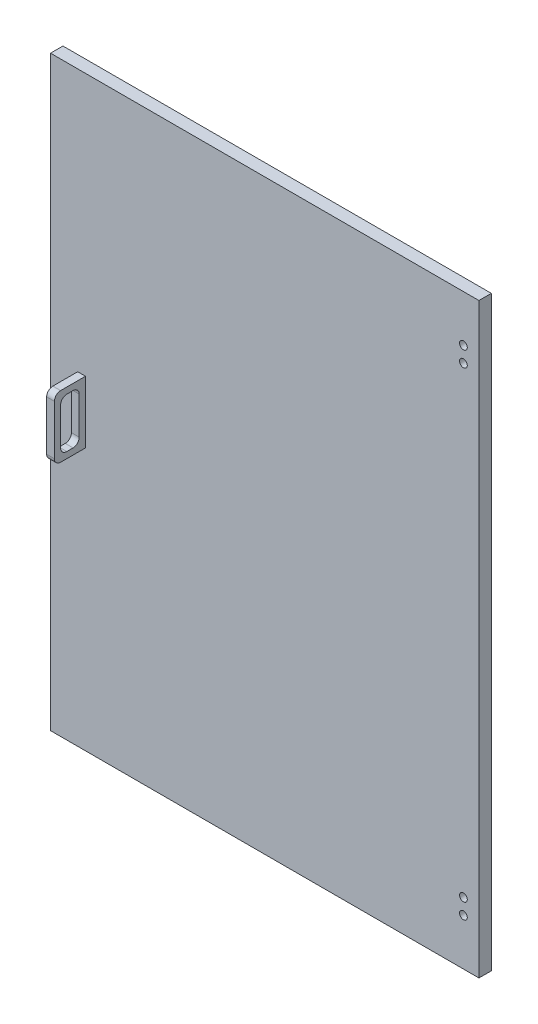
SolidWorks part; units mm, degrees
material "PVC 0.007 Plasticized"
ref_plane "Front Plane" through (0, 0, 0) normal (0, 0, 1) x (1, 0, 0)
ref_plane "Top Plane" through (0, 0, 0) normal (0, 1, 0) x (1, 0, 0)
ref_plane "Right Plane" through (0, 0, 0) normal (1, 0, 0) x (0, 0, -1)
sketch "Sketch1" plane through (0, 0, 0) normal (0, 0, 1) x (1, 0, 0)
  line L0 (-87.63, 120.015) -> (87.63, 120.015)
  line L7 (-87.63, 120.015) -> (-87.63, -120.015)
  line L8 (-87.63, -120.015) -> (87.63, -120.015)
  line L9 (87.63, 120.015) -> (87.63, -120.015)
  point P0 (0, 0)
  dimension "D1" = 240.03
  dimension "D2" = 175.26
  dimension "D3" = 87.63
  dimension "D4" = 120.015
extrude "Boss-Extrude1" add sketch "Sketch1" against normal blind 5.08
sketch "Sketch2" plane through (0, 0, 0) normal (0, 0, 1) x (1, 0, 0)
  line L0 (87.63, -120.015) -> (87.63, 120.015) construction
  line L1 (87.63, 120.015) -> (-87.63, 120.015) construction
  line L2 (2.794, 0) -> (-2.794, 0) construction
  circle A0 centre (81.28, 100.965) radius 1.5875
  circle A1 centre (81.28, 94.615) radius 1.5875
  circle A2 centre (81.28, -94.615) radius 1.5875
  circle A3 centre (81.28, -100.965) radius 1.5875
  point P10 (81.28, -94.615)
  dimension "D1" = 3.175
  dimension "D2" = 3.175
  dimension "D3" = 6.35
  dimension "D4" = 19.05
  dimension "D5" = 6.35
extrude "Cut-Extrude1" cut sketch "Sketch2" against normal through all
sketch "Sketch3" plane through (0, 0, 0) normal (0, 0, 1) x (1, 0, 0)
  line L0 (2.794, 0) -> (-2.794, 0) construction
  line L1 (-76.5175, -12.7) -> (-73.3425, -12.7)
  line L2 (-76.5175, -12.7) -> (-76.5175, 12.7)
  line L3 (-76.5175, 12.7) -> (-73.3425, 12.7)
  line L4 (-73.3425, -12.7) -> (-73.3425, 12.7)
  line L5 (-76.5175, -12.7) -> (-73.3425, 12.7) construction
  line L6 (-76.5175, 12.7) -> (-73.3425, -12.7) construction
  line L7 (-87.63, 120.015) -> (-87.63, -120.015) construction
  point P0 (-74.93, 0)
  dimension "D1" = 25.4
  dimension "D2" = 3.175
  dimension "D3" = 12.7
extrude "Boss-Extrude2" add sketch "Sketch3" along normal blind 12.7
sketch "Sketch4" plane through (-73.3425, 0, 0) normal (1, 0, 0) x (0, 0, -1)
  line L0 (9.779, 0) -> (-9.779, 0) construction
  line L1 (-10.16, -10.16) -> (-2.54, -10.16)
  line L2 (-10.16, -10.16) -> (-10.16, 10.16)
  line L3 (-10.16, 10.16) -> (-2.54, 10.16)
  line L4 (-2.54, -10.16) -> (-2.54, 10.16)
  line L5 (-10.16, -10.16) -> (-2.54, 10.16) construction
  line L6 (-10.16, 10.16) -> (-2.54, -10.16) construction
  line L7 (-12.7, -12.7) -> (-12.7, 12.7) construction
  line L8 (0, 143.3597) -> (0, -143.3597) construction
  line L9 (-12.7, 12.7) -> (0, 12.7) construction
  point P0 (-6.35, 0)
  dimension "D1" = 2.54
  dimension "D2" = 2.54
  dimension "D3" = 2.54
extrude "Cut-Extrude2" cut sketch "Sketch4" against normal through all
fillet "Fillet1" radius 2.54 6 edges at (-74.93, -12.7, 12.7) (-74.93, 12.7, 12.7) (-74.93, -10.16, 10.16) (-74.93, -10.16, 2.54) (-74.93, 10.16, 10.16) (-74.93, 10.16, 2.54)
